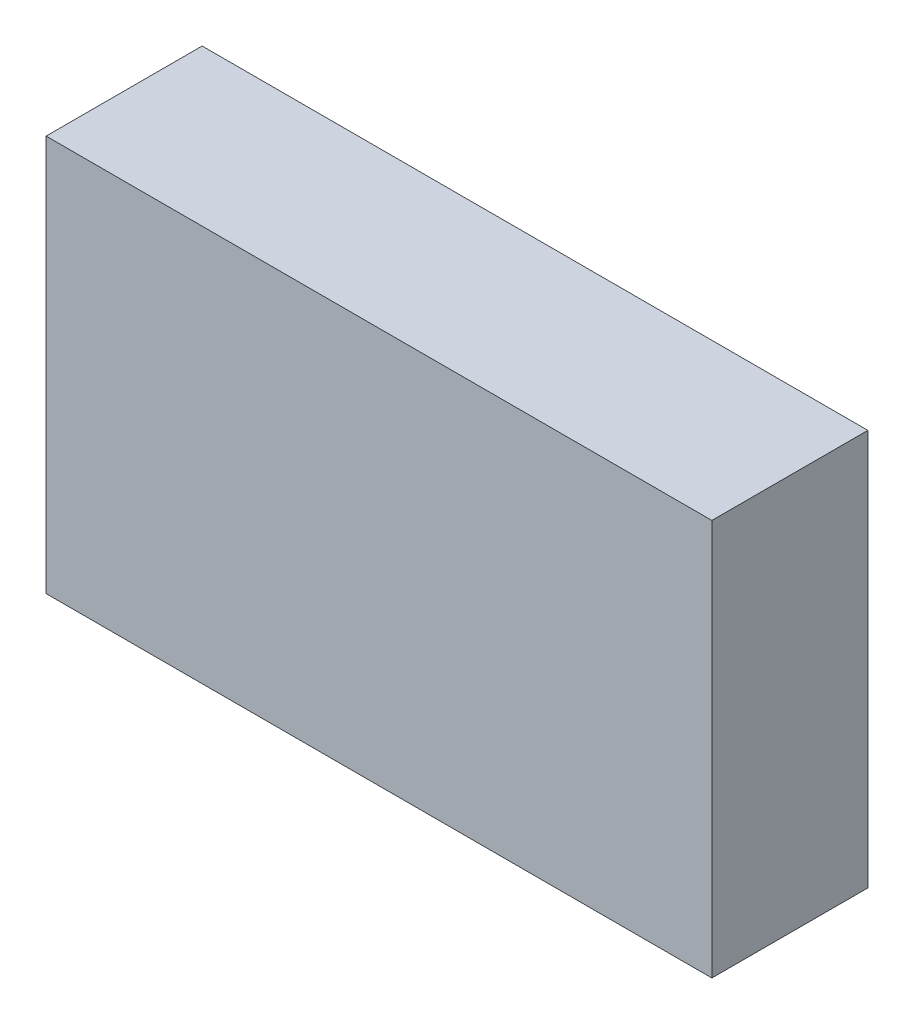
SolidWorks part; units mm, degrees
ref_plane "Front Plane" through (0, 0, 0) normal (0, 0, 1) x (1, 0, 0)
ref_plane "Top Plane" through (0, 0, 0) normal (0, 1, 0) x (1, 0, 0)
ref_plane "Right Plane" through (0, 0, 0) normal (1, 0, 0) x (0, 0, -1)
sketch "Sketch1" plane through (0, 0, 0) normal (0, 0, 1) x (1, 0, 0)
  line L0 (-1.778, 1.27) -> (2.4892, 1.27)
  line L1 (2.4892, 1.27) -> (2.4892, -1.27)
  line L2 (2.4892, -1.27) -> (-1.778, -1.27)
  line L3 (-1.778, -1.27) -> (-1.778, 1.27)
extrude "Component_Outline" add sketch "Sketch1" along normal blind 1 separate body
sketch3d "3DSketch1"
  line L0 (0, 0, 0) -> (1, 0, 0)
  line L1 (0, 0, 0) -> (0, 1, 0)
  line L2 (0, 0, 0) -> (0, 0, 1)
  point P0 (0, 0, 0)
